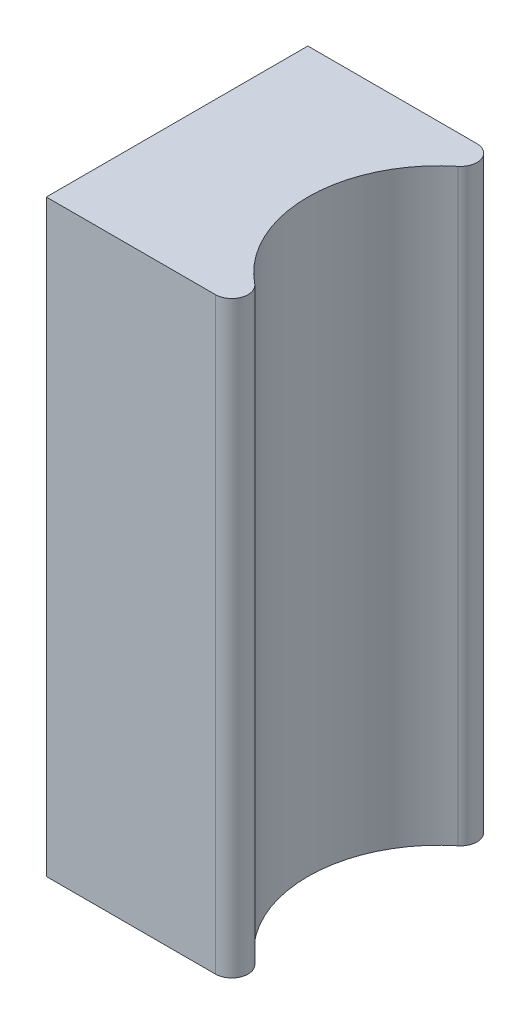
SolidWorks part; units mm, degrees
material "ABS"
ref_plane "Front Plane" through (0, 0, 0) normal (0, 0, 1) x (1, 0, 0)
ref_plane "Top Plane" through (0, 0, 0) normal (0, 1, 0) x (1, 0, 0)
ref_plane "Right Plane" through (0, 0, 0) normal (1, 0, 0) x (0, 0, -1)
sketch "Sketch3" plane through (0, 0, 0) normal (0, 1, 0) x (1, 0, 0)
  line L0 (-27.7812, 0) -> (-27.7812, 25.4)
  line L1 (-27.7812, 25.4) -> (-11.3615, 25.4)
  line L3 (-27.7812, 0) -> (-11.3615, 0)
  arc A0 (-11.3615, 0) -> (-10.3637, 2.8222) centre (-11.3615, 1.5875) ccw
  arc A1 (-11.3615, 25.4) -> (-10.3637, 22.5778) centre (-11.3615, 23.8125) cw
  arc A2 (-10.3637, 22.5778) -> (-10.3637, 2.8222) centre (-2.3813, 12.7) ccw
extrude "Boss-Extrude1" add sketch "Sketch3" along normal blind 57.15
